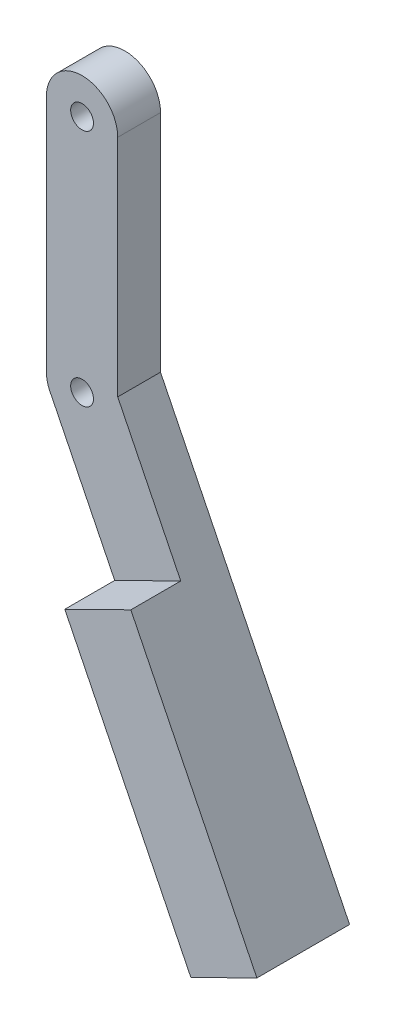
SolidWorks part; units mm, degrees
ref_plane "Alzado" through (0, 0, 0) normal (0, 0, 1) x (1, 0, 0)
ref_plane "Planta" through (0, 0, 0) normal (0, 1, 0) x (1, 0, 0)
ref_plane "Vista lateral" through (0, 0, 0) normal (1, 0, 0) x (0, 0, -1)
sketch "Croquis1" plane through (0, 0, 0) normal (0, 0, 1) x (1, 0, 0)
  line L0 (0, 0) -> (0, 33.48) construction
  line L1 (5, 1.95) -> (-4.2625, -2.6137) construction
  line L3 (-5, 33.48) -> (-5, 0)
  line L5 (5, 33.48) -> (5, 0)
  line L6 (5, 1.95) -> (31.5185, -51.8716)
  line L7 (-4.2625, -2.6137) -> (22.2561, -56.4353)
  line L8 (31.5185, -51.8716) -> (22.2561, -56.4353)
  arc A0 (5, 33.48) -> (-5, 33.48) centre (0, 33.48) ccw
  arc A1 (-5, 0) -> (5, 0) centre (0, 0) ccw
  point P12 (0, 38.48)
  dimension "D1" = 33.48
  dimension "D2" = 10
  dimension "D3" = 153.77
  dimension "D4" = 1.95
  dimension "D5" = 60
extrude "Saliente-Extruir1" add sketch "Croquis1" along normal blind 6 contours L3 A1 L5 A0 | A1 L7 L8 L6 L5
sketch "Croquis2" plane through (0, 0, 6) normal (0, 0, 1) x (1, 0, 0)
  circle A0 centre (0, 33.48) radius 1.6
  circle A1 centre (0, 0) radius 1.6
  dimension "D1" = 3.2
  dimension "D2" = 3.2
extrude "Cortar-Extruir1" cut sketch "Croquis2" against normal through all
sketch "Croquis3" plane through (0, 0, 6) normal (0, 0, -1) x (-1, 0, 0)
  line L0 (-31.5185, -51.8716) -> (-22.2561, -56.4353)
  line L1 (-31.5185, -51.8716) -> (-13.8395, -15.9905)
  line L2 (-22.2561, -56.4353) -> (-4.5771, -20.5543)
  line L3 (-13.8395, -15.9905) -> (-4.5771, -20.5543)
  dimension "D1" = 40
extrude "Saliente-Extruir2" add sketch "Croquis3" against normal blind 7
